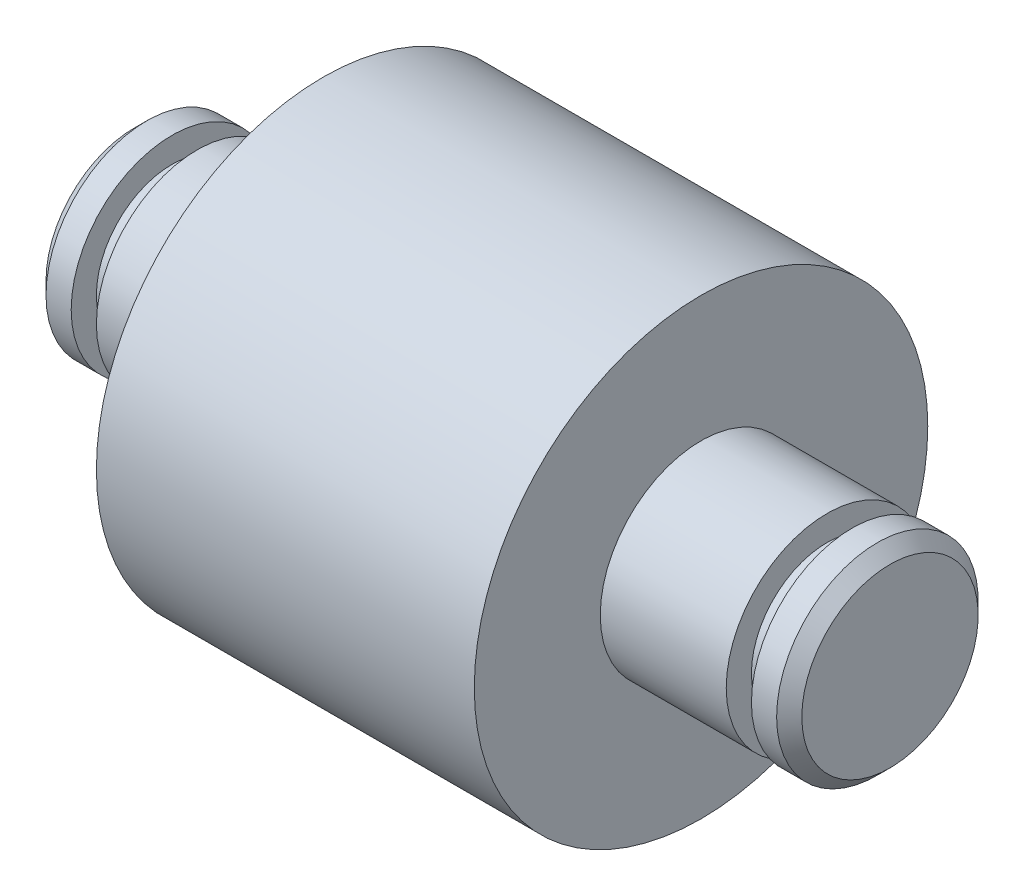
SolidWorks part; units mm, degrees
ref_plane "Front Plane" through (0, 0, 0) normal (0, 0, 1) x (1, 0, 0)
ref_plane "Top Plane" through (0, 0, 0) normal (0, 1, 0) x (1, 0, 0)
ref_plane "Right Plane" through (0, 0, 0) normal (1, 0, 0) x (0, 0, -1)
sketch "Sketch1" plane through (0, 0, 0) normal (0, 0, 1) x (1, 0, 0)
  line L0 (0, 0) -> (67.3913, 0) construction
  line L1 (0, 0) -> (0, 3.5)
  line L2 (0.5, 4) -> (1.5, 4)
  line L3 (1.5, 4) -> (1.5, 3)
  line L4 (1.5, 3) -> (2.5, 3)
  line L5 (2.5, 3) -> (2.5, 4)
  line L6 (2.5, 4) -> (7.5, 4)
  line L7 (7.5, 4) -> (7.5, 9)
  line L8 (7.5, 9) -> (22.5, 9)
  line L9 (22.5, 9) -> (22.5, 4)
  line L10 (22.5, 4) -> (27.5, 4)
  line L11 (27.5, 4) -> (27.5, 3)
  line L12 (27.5, 3) -> (28.5, 3)
  line L13 (28.5, 3) -> (28.5, 4)
  line L14 (28.5, 4) -> (29.5, 4)
  line L15 (30, 3.5) -> (30, 0)
  line L16 (0, 3.5) -> (0.5, 4)
  line L17 (29.5, 4) -> (30, 3.5)
  line L18 (0, 0) -> (30, 0)
  point P4 (0, 4)
  point P17 (30, 4)
  point P22 (0.5074, 0.5265)
  point P23 (0, 0)
  dimension "D1" = 4
  dimension "D2" = 1
  dimension "D3" = 1
  dimension "D4" = 1
  dimension "D5" = 7.5
  dimension "D6" = 9
  dimension "D7" = 4
  dimension "D8" = 7.5
  dimension "D9" = 4
  dimension "D10" = 1
  dimension "D11" = 1
  dimension "D12" = 15
  dimension "D13" = 1.5
  dimension "D14" = 1.5
  dimension "D15" = 0.5
  dimension "D16" = 45
  dimension "D17" = 0.5
  dimension "D18" = 45
revolve "Revolve1" add sketch "Sketch1" angle 360 about L0
